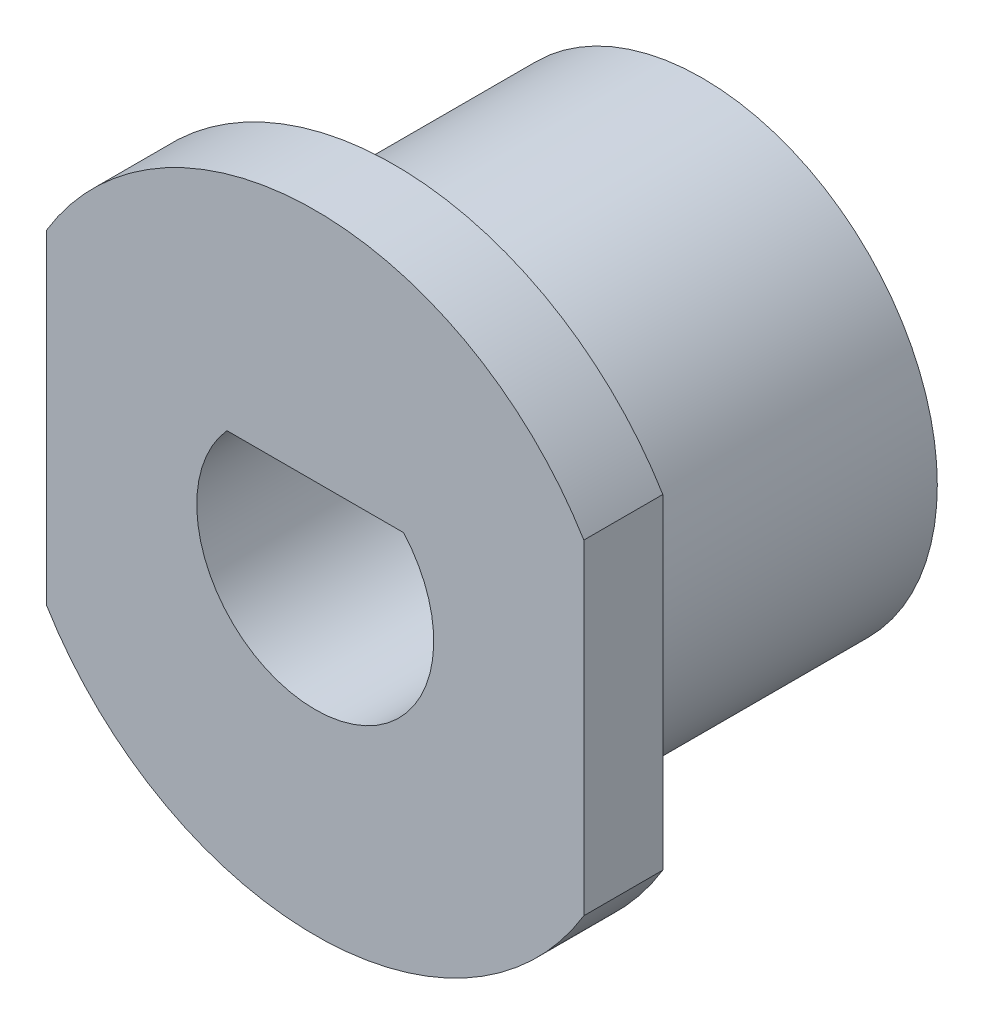
SolidWorks part; units mm, degrees
ref_plane "Front Plane" through (0, 0, 0) normal (0, 0, 1) x (1, 0, 0)
ref_plane "Top Plane" through (0, 0, 0) normal (0, 1, 0) x (1, 0, 0)
ref_plane "Right Plane" through (0, 0, 0) normal (1, 0, 0) x (0, 0, -1)
sketch "Sketch1" plane through (0, 0, 0) normal (0, 0, 1) x (1, 0, 0)
  line L0 (1.118, 1) -> (-1.118, 1)
  circle A0 centre (0, 0) radius 1.5
  circle A1 centre (0, 0) radius 2.975
  dimension "D1" = 3
  dimension "D3" = 5.95
  dimension "D2" = 1
extrude "Boss-Extrude1" add sketch "Sketch1" along normal blind 4.9 contours A1 A0 | L0 A0
sketch "Sketch2" plane through (0, 0, 4.9) normal (0, 0, 1) x (1, 0, 0)
  line L0 (3.4, 2.0593) -> (3.4, -2.0593)
  line L1 (0, 0) -> (0, 0.7295) construction
  line L2 (-3.4, 2.0593) -> (-3.4, -2.0593)
  circle A0 centre (0, 0) radius 2.975 construction
  circle A1 centre (0, 0) radius 2.975
  circle A2 centre (0, 0) radius 3.975
  circle M3 centre (0, 0) radius 2.975
  dimension "D1" = 7.95
  dimension "D2" = 3.4
extrude "Boss-Extrude2" add sketch "Sketch2" against normal blind 1 contours L0 A2 L2 M3
